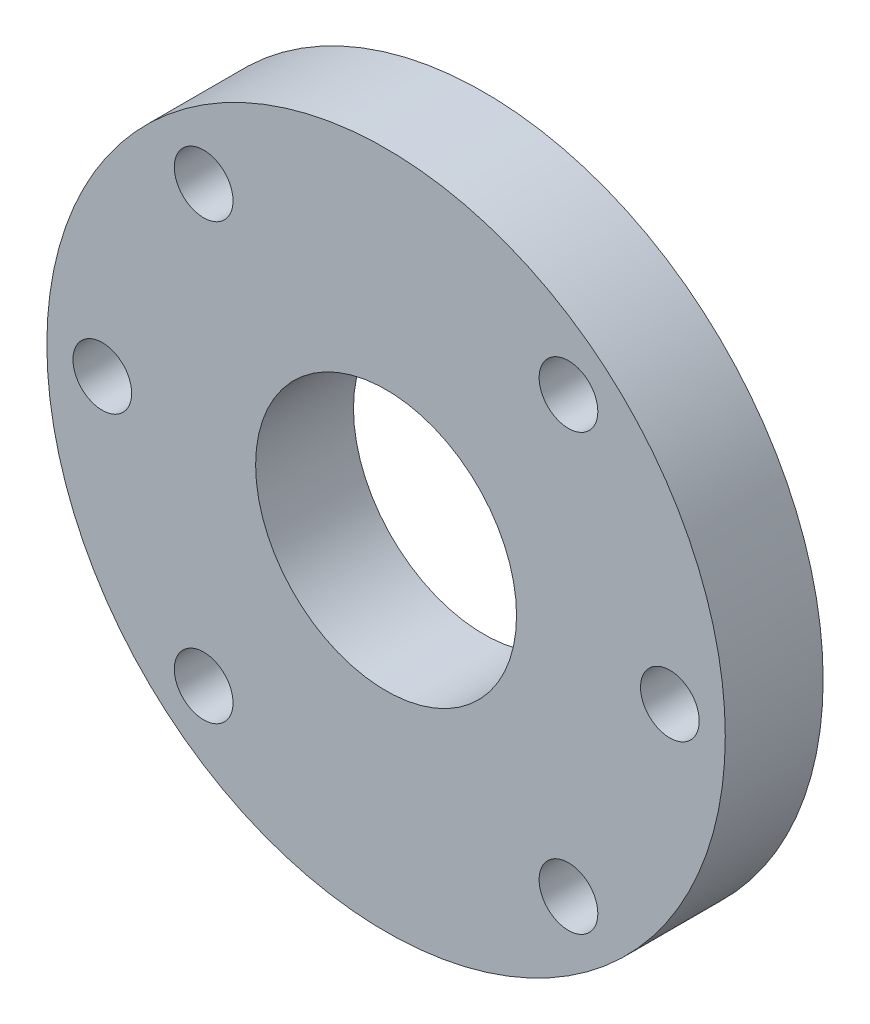
SolidWorks part; units mm, degrees
material "ABS"
ref_plane "前视基准面" through (0, 0, 0) normal (0, 0, 1) x (1, 0, 0)
ref_plane "上视基准面" through (0, 0, 0) normal (0, 1, 0) x (1, 0, 0)
ref_plane "右视基准面" through (0, 0, 0) normal (1, 0, 0) x (0, 0, -1)
sketch "草图1" plane through (0, 0, 0) normal (0, 0, 1) x (1, 0, 0)
  line L0 (-21.75, 0) -> (21.75, 0) construction
  line L1 (0, 0) -> (-13.9806, -16.6615) construction
  line L2 (0, 0) -> (13.9806, 16.6615) construction
  line L3 (-13.9806, 16.6615) -> (0, 0) construction
  line L4 (0, 0) -> (13.9806, -16.6615) construction
  circle A0 centre (0, 0) radius 21.75 construction
  circle A1 centre (0, 0) radius 26
  circle A2 centre (-21.75, 0) radius 2.25
  circle A3 centre (-13.9806, 16.6615) radius 2.25
  circle A4 centre (-13.9806, -16.6615) radius 2.25
  circle A5 centre (13.9806, -16.6615) radius 2.25
  circle A6 centre (21.75, 0) radius 2.25
  circle A7 centre (13.9806, 16.6615) radius 2.25
  dimension "D1" = 52
  dimension "D2" = 43.5
  dimension "D7" = 4.5
  dimension "D3" = 50
extrude "凸台-拉伸1" add sketch "草图1" along normal blind 7.5
sketch "草图2" plane through (0, 0, 7.5) normal (0, 0, 1) x (1, 0, 0)
  circle A0 centre (0, 0) radius 10
  dimension "D1" = 20
extrude "切除-拉伸1" cut sketch "草图2" against normal through all
